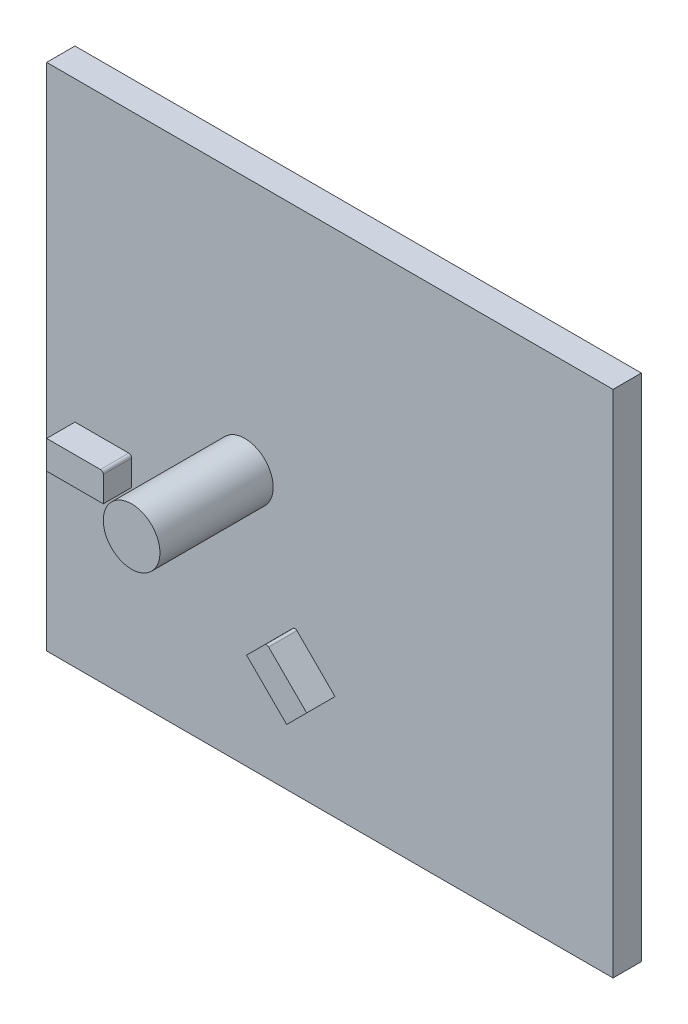
SolidWorks part; units mm, degrees
material "PE haute densité"
ref_plane "Plan de face" through (0, 0, 0) normal (0, 0, 1) x (1, 0, 0)
ref_plane "Plan de dessus" through (0, 0, 0) normal (0, 1, 0) x (1, 0, 0)
ref_plane "Plan de droite" through (0, 0, 0) normal (1, 0, 0) x (0, 0, -1)
sketch "Esquisse1" plane through (0, 0, 0) normal (0, 0, 1) x (1, 0, 0)
  line L1 (100, 90) -> (-100, 90)
  line L2 (100, 90) -> (100, -90)
  line L3 (100, -90) -> (-100, -90)
  line L4 (-100, 90) -> (-100, -90)
  line L5 (100, 90) -> (-100, -90) construction
  line L6 (100, -90) -> (-100, 90) construction
  circle A0 centre (-30, 0) radius 10
  dimension "D1" = 20
  dimension "D2" = 200
  dimension "D3" = 180
  dimension "D4" = 30
extrude "Boss.-Extru.1" add sketch "Esquisse1" along normal blind 10
sketch "Esquisse3" plane through (0, 0, 0) normal (0, 0, -1) x (-1, 0, 0)
  circle A1 centre (30, 0) radius 10
extrude "Boss.-Extru.2" add sketch "Esquisse3" against normal blind 50
sketch "Esquisse4" plane through (0, 0, 10) normal (0, 0, 1) x (1, 0, 0)
  line L1 (-70, -25) -> (-90, -25)
  line L2 (-70, -25) -> (-70, -15)
  line L3 (-70, -15) -> (-90, -15)
  line L4 (-90, -25) -> (-90, -15)
  line L5 (-70, -25) -> (-90, -15) construction
  line L6 (-70, -15) -> (-90, -25) construction
  line L7 (-12.3223, -38.8909) -> (1.8198, -53.033)
  line L8 (-12.3223, -38.8909) -> (-19.3934, -45.9619)
  line L9 (1.8198, -53.033) -> (-5.2513, -60.1041)
  line L10 (-19.3934, -45.9619) -> (-5.2513, -60.1041)
  circle A0 centre (-30, 0) radius 10 construction
  point P0 (-80, -20)
  dimension "D1" = 15
  dimension "D2" = 20
  dimension "D3" = 10
  dimension "D4" = 40
  dimension "D5" = 20
  dimension "D6" = 10
  dimension "D7" = 45
  dimension "D8" = 15
  dimension "D9" = 40
extrude "Boss.-Extru.3" add sketch "Esquisse4" along normal blind 10
fillet "Congé1" radius 1 2 edges at (-70, -15, 15) (-12.3223, -38.8909, 15)
